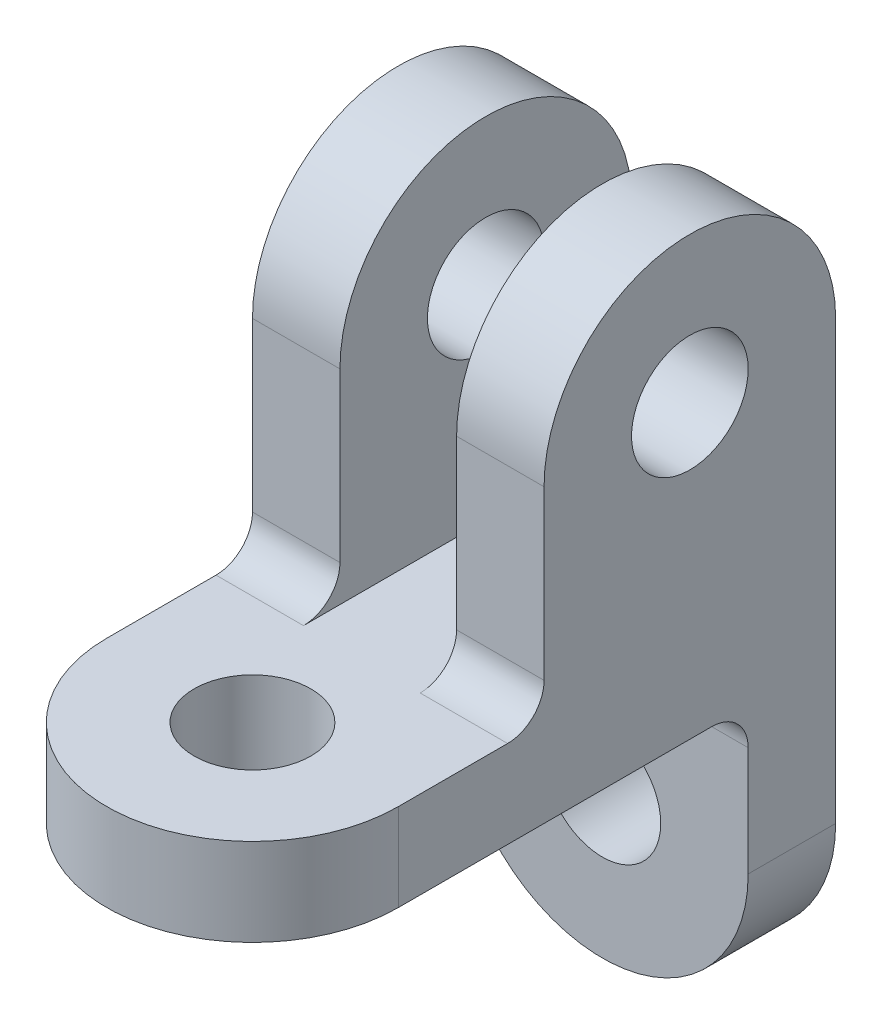
SolidWorks part; units mm, degrees
ref_plane "Front Plane" through (0, 0, 0) normal (0, 0, 1) x (1, 0, 0)
ref_plane "Top Plane" through (0, 0, 0) normal (0, 1, 0) x (1, 0, 0)
ref_plane "Right Plane" through (0, 0, 0) normal (1, 0, 0) x (0, 0, -1)
sketch "Sketch1" plane through (0, 0, 0) normal (0, 0, 1) x (1, 0, 0)
  line L0 (0, 0) -> (0, 20)
  line L1 (0, 0) -> (40, 0) construction
  line L2 (40, 0) -> (40, 20)
  line L3 (20, 0) -> (20, 60) construction
  line L4 (0, 20) -> (40, 20)
  arc A0 (0, 0) -> (40, 0) centre (20, 0) ccw
  circle A1 centre (20, 0) radius 8
  dimension "D2" = 16
  dimension "D1" = 40
  dimension "D3" = 60
  dimension "D4" = 20
  dimension "D5" = 20
extrude "Boss-Extrude1" add sketch "Sketch1" along normal blind 12
sketch "Sketch2" plane through (0, 20, 0) normal (0, 1, 0) x (1, 0, 0)
  line L0 (40, -12) -> (40, 0) construction
  line L1 (0, 0) -> (40, 0)
  line L2 (0, 0) -> (0, -60)
  line L4 (40, 0) -> (40, -60)
  line L5 (20, -80) -> (20, 0) construction
  arc A0 (0, -60) -> (40, -60) centre (20, -60) ccw
  circle A1 centre (20, -60) radius 8
  point P9 (20, -60)
  dimension "D3" = 16
  dimension "D1" = 60
  dimension "D2" = 20
extrude "Boss-Extrude2" add sketch "Sketch2" along normal blind 12
sketch "Sketch3" plane through (0, 0, 0) normal (0, 0, -1) x (-1, 0, 0)
  line L1 (-40, 32) -> (-28, 32)
  line L5 (0, 32) -> (-12, 32)
  line L9 (0, 80) -> (-12, 80)
  line L12 (-40, 80) -> (-28, 80)
  line L14 (-40, 80) -> (-40, 32)
  line L15 (-28, 80) -> (-28, 32)
  line L16 (0, 80) -> (0, 32)
  line L17 (-12, 80) -> (-12, 32)
  point P16 (-40, 80)
  point P17 (-28, 80)
  dimension "D1" = 12
  dimension "D2" = 16
extrude "Boss-Extrude3" add sketch "Sketch3" against normal blind 40
sketch "Sketch4" plane through (40, 0, 0) normal (1, 0, 0) x (0, 0, -1)
  line L0 (-20, 80) -> (-20, 60) construction
  line L1 (-40, 80) -> (0, 80) construction
  line L11 (0, 0) -> (0, 80)
  line L12 (0, 80) -> (-40, 80)
  line L13 (-40, 80) -> (-40, 32)
  line L14 (-40, 32) -> (-60, 32)
  line L15 (-60, 32) -> (-60, 20)
  line L16 (-60, 20) -> (-12, 20)
  line L17 (-12, 20) -> (-12, 0)
  line L18 (-12, 0) -> (0, 0)
  line L19 (0, 60) -> (0, 80)
  line L20 (0, 80) -> (-40, 80)
  line L21 (-40, 80) -> (-40, 60)
  arc A0 (0, 60) -> (-40, 60) centre (-20, 60) ccw
  circle A1 centre (-20, 60) radius 8
  dimension "D2" = 0
  dimension "D1" = 16
extrude "Cut-Extrude1" cut sketch "Sketch4" against normal blind 40
fillet "Fillet1" radius 5 3 edges at (34, 32, 40) (6, 32, 40) (20, 20, 12)
